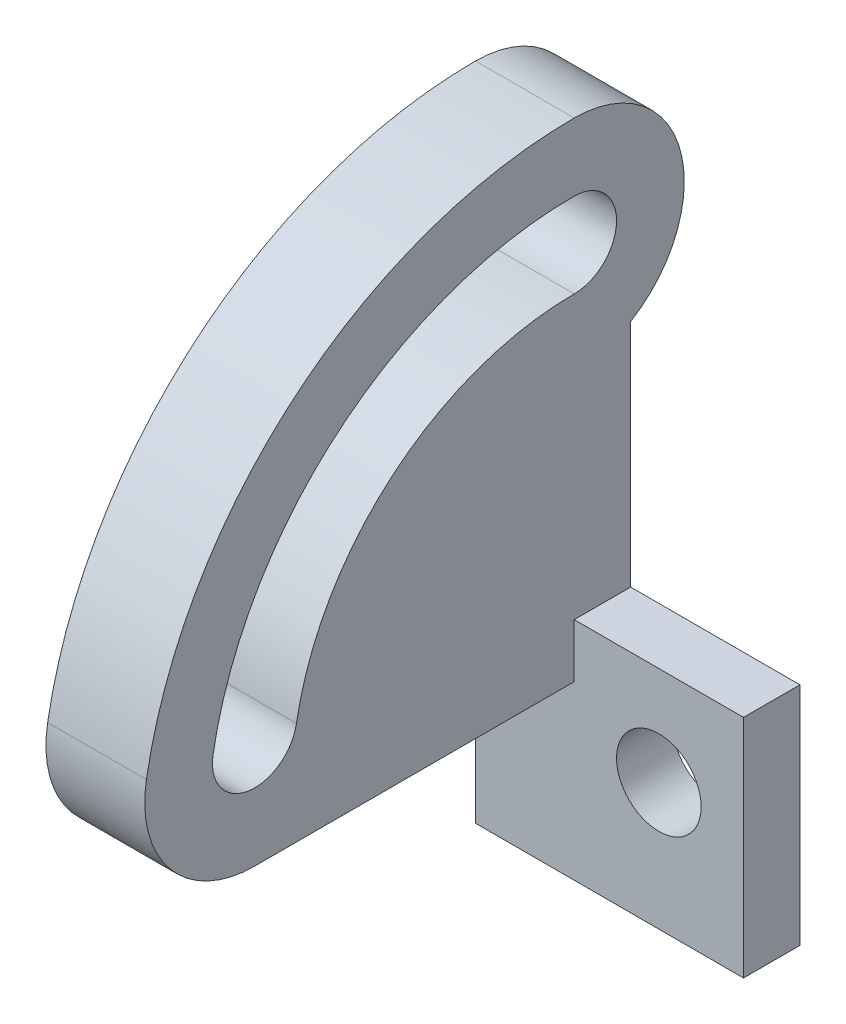
SolidWorks part; units mm, degrees
ref_plane "Alzado" through (0, 0, 0) normal (0, 0, 1) x (1, 0, 0)
ref_plane "Planta" through (0, 0, 0) normal (0, 1, 0) x (1, 0, 0)
ref_plane "Vista lateral" through (0, 0, 0) normal (1, 0, 0) x (0, 0, -1)
sketch "Croquis1" plane through (0, 0, 0) normal (0, 0, 1) x (1, 0, 0)
  line L0 (-27.8873, 15.5366) -> (-27.8873, -12.4634) construction
  line L1 (-40.8873, 15.5366) -> (-14.8873, 15.5366)
  line L2 (-40.8873, 15.5366) -> (-40.8873, -12.4634)
  line L3 (-40.8873, -12.4634) -> (-14.8873, -12.4634)
  line L4 (-14.8873, 15.5366) -> (-14.8873, -12.4634)
  circle A0 centre (-37.3873, 12.0366) radius 1.5
  circle A1 centre (-18.3873, 12.0366) radius 1.5
  circle A2 centre (-27.8873, -5.4634) radius 1.5
  point P6 (-27.8873, 15.5366)
  dimension "D3" = 9.5
  dimension "D5" = 21
  dimension "D1" = 26
  dimension "D2" = 28
  dimension "D4" = 3.5
extrude "Saliente-Extruir1" add sketch "Croquis1" along normal blind 2
sketch "Croquis2" plane through (-40.8873, 0, 0) normal (-1, 0, 0) x (0, 0, 1)
  circle A0 centre (9.3742, 24.3586) radius 2.5 construction
  circle A1 centre (9.3742, 24.3586) radius 2.5
sketch "Croquis7" plane through (0, 0, 2) normal (0, 0, 1) x (1, 0, 0)
  line L1 (-40.8873, 15.5366) -> (-43.8873, 15.5366)
  line L2 (-40.8873, 15.5366) -> (-40.8873, 7.5366)
  line L3 (-40.8873, 7.5366) -> (-43.8873, 7.5366)
  line L4 (-43.8873, 15.5366) -> (-43.8873, 7.5366)
  dimension "D1" = 3
  dimension "D2" = 8
extrude "Saliente-Extruir3" add sketch "Croquis7" against normal up to vertex (2 mm away)
sketch "Croquis4" plane through (-40.8873, 0, 0) normal (-1, 0, 0) x (0, 0, 1)
  line L3 (0, 15.5366) -> (0, 23.6866)
  line L4 (13.3234, 13.6332) -> (2, 13.6332)
  line L5 (2, 7.5366) -> (2, -12.4634) construction
  line L6 (2, 13.6332) -> (2, 15.5366)
  line L7 (2, 15.5366) -> (0, 15.5366)
  circle A0 centre (9.3742, 24.3586) radius 1.5 construction
  arc A1 (14.8006, 17.7937) -> (2, 28.5347) centre (2, 15.5366) ccw
  arc A2 (11.8462, 17.2727) -> (2, 25.5347) centre (2, 15.5366) ccw
  arc A3 (11.8462, 17.2727) -> (14.8006, 17.7937) centre (13.3234, 17.5332) ccw
  arc A4 (2, 28.5347) -> (2, 25.5347) centre (2, 27.0347) ccw
  arc A5 (17.1642, 18.2104) -> (2, 30.9347) centre (2, 15.5366) ccw
  arc A6 (2, 30.9347) -> (0, 23.6866) centre (2, 27.0347) ccw
  arc A8 (13.3234, 13.6332) -> (17.1642, 18.2104) centre (13.3234, 17.5332) ccw
  arc A10 (9.4827, 16.856) -> (17.1642, 18.2104) centre (13.3234, 17.5332) ccw construction
  arc A11 (9.4827, 16.856) -> (2, 23.1347) centre (2, 15.5366) ccw construction
  arc A12 (2, 30.9347) -> (2, 23.1347) centre (2, 27.0347) ccw construction
  point P27 (0, 0)
  dimension "D1" = 2.4
  dimension "D2" = 3
extrude "Saliente-Extruir2" add sketch "Croquis4" along normal blind 3 and the other way blind 0.5
sketch "Croquis5" plane through (0, 0, 2) normal (0, 0, 1) x (1, 0, 0)
  line L1 (-14.8873, 15.5366) -> (-40.3873, 15.5366) construction
  line L2 (-34.3873, 15.5366) -> (-34.3873, 7.5366)
  line L3 (-34.3873, 7.5366) -> (-40.8873, 7.5366)
  line L4 (-40.8873, 7.5366) -> (-40.8873, -12.4634) construction
  line L5 (-40.8873, 7.5366) -> (-40.8873, -12.4634)
  line L6 (-40.8873, -12.4634) -> (-14.8873, -12.4634)
  line L7 (-14.8873, -12.4634) -> (-14.8873, 15.5366)
  line L8 (-14.8873, 15.5366) -> (-34.3873, 15.5366)
  circle A0 centre (-37.3873, 12.0366) radius 1.5 construction
  dimension "D1" = 3
  dimension "D2" = 8
extrude "Cortar-Extruir1" cut sketch "Croquis5" against normal up to vertex (2 mm away) up to point (-40.8873, -12.4634, 0)
